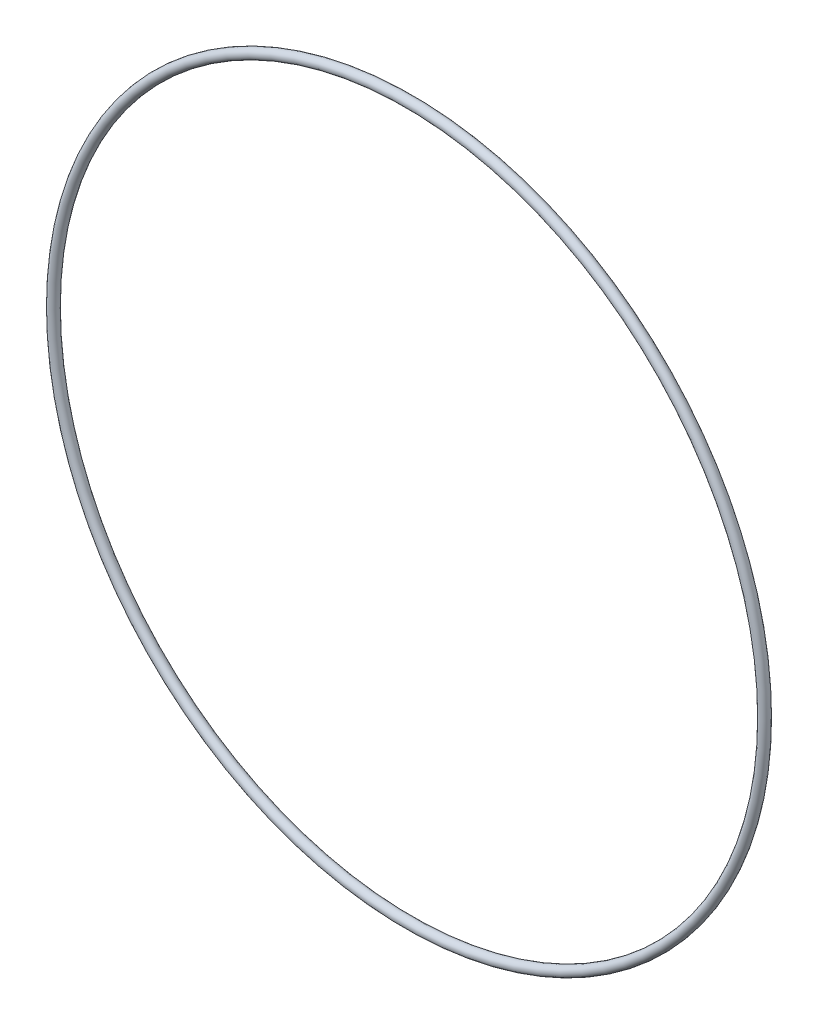
SolidWorks part; units mm, degrees
ref_plane "Front Plane" through (0, 0, 0) normal (0, 0, 1) x (1, 0, 0)
ref_plane "Top Plane" through (0, 0, 0) normal (0, 1, 0) x (1, 0, 0)
ref_plane "Right Plane" through (0, 0, 0) normal (1, 0, 0) x (0, 0, -1)
sketch "Sketch1" plane through (0, 0, 0) normal (0, 0, 1) x (1, 0, 0)
  line L0 (-65.1383, 0) -> (65.1383, 0) construction
  line L1 (-63.3603, 0) -> (63.3603, 0) construction
  line L2 (-46.0597, 46.0597) -> (46.0597, -46.0597) construction
  point P3 (63.3603, 0)
  point P4 (0, 0)
  point P8 (0, 0)
  point P9 (0, 0)
  point P10 (-65.1383, 0)
  point P11 (-63.3603, 0)
  point P14 (0, 0)
  point P15 (46.0597, -46.0597)
  point P16 (65.1383, 0)
  dimension "Actual OD" = 130.2766
  dimension "Actual ID" = 126.7206
  dimension "Actual Width" = 1.778
  dimension "D1" = 45
sketch "Sketch2" plane through (0, 0, 0) normal (0, 1, 0) x (1, 0, 0)
  line L0 (-65.1383, 0) -> (65.1383, 0) construction
  line L1 (-64.2493, 0.889) -> (-64.2493, -0.889) construction
  line L2 (0, -0.889) -> (0, 0.889) construction
  circle A0 centre (-64.2493, 0) radius 0.889
  point P12 (0, 0)
revolve "Revolve1" add sketch "Sketch2" angle 360 about L2
sketch "Sketch3" plane through (0, 0, 0) normal (1, 0, 0) x (0, 0, -1)
  line L0 (-0.889, 0) -> (0.889, 0) construction
  line L1 (-0.889, -47.5202) -> (-0.889, 47.5202) construction
  point P4 (0, 0)
  point P7 (-0.889, 0)
  point P9 (-0.889, -47.5202)
  dimension "D1" = 1.778
  dimension "D2" = 95.0404
equation "\"D1@Sketch3\"=\"Actual Width@Sketch1\""
equation "\"D2@Sketch3\"=\"Actual ID@Sketch1\"*.75"
